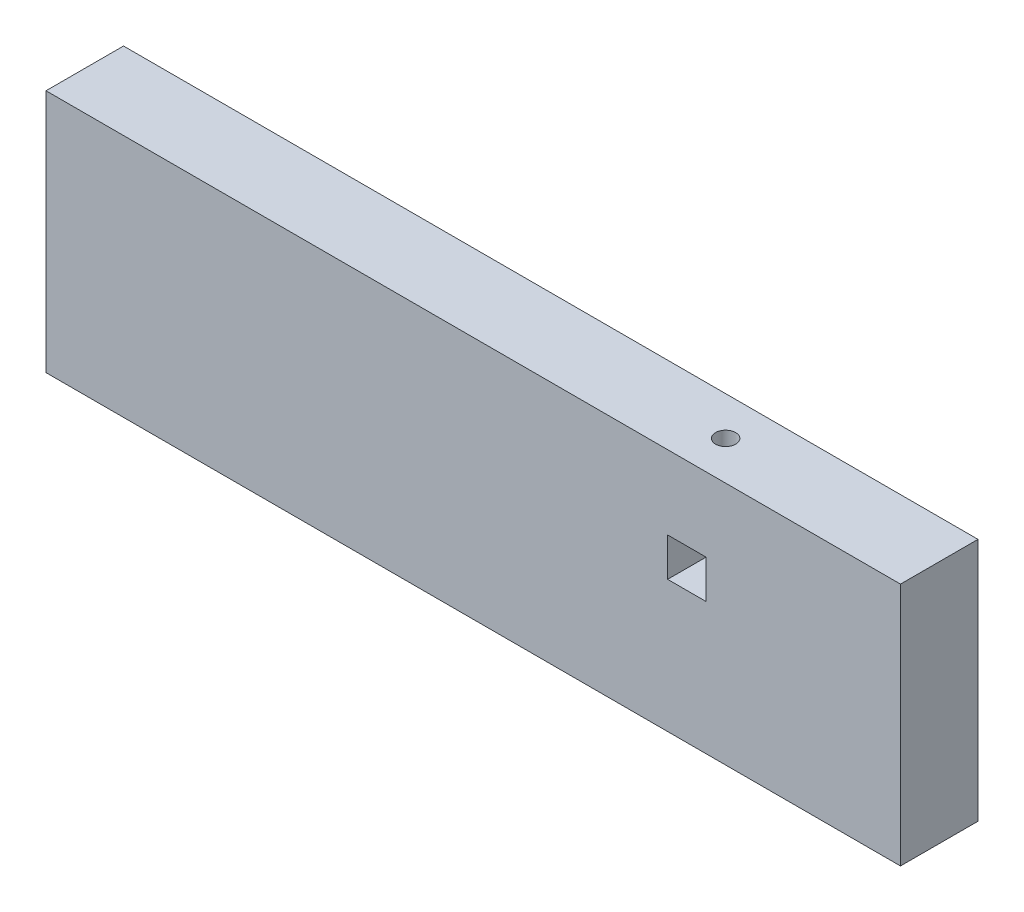
SolidWorks part; units mm, degrees
material "ABS"
ref_plane "Front Plane" through (0, 0, 0) normal (0, 0, 1) x (1, 0, 0)
ref_plane "Top Plane" through (0, 0, 0) normal (0, 1, 0) x (1, 0, 0)
ref_plane "Right Plane" through (0, 0, 0) normal (1, 0, 0) x (0, 0, -1)
sketch "Sketch1" plane through (0, 0, 0) normal (0, 0, 1) x (1, 0, 0)
  line L1 (-70, 40) -> (70, 40)
  line L2 (-70, 40) -> (-70, 0)
  line L3 (-70, 0) -> (70, 0)
  line L4 (70, 40) -> (70, 0)
  line L5 (31.85, 27.9) -> (38.15, 27.9)
  line L6 (31.85, 27.9) -> (31.85, 21.6)
  line L7 (31.85, 21.6) -> (38.15, 21.6)
  line L8 (38.15, 27.9) -> (38.15, 21.6)
  line L9 (32, 27.75) -> (38, 27.75) construction
  line L10 (32, 27.75) -> (32, 21.75) construction
  line L11 (32, 21.75) -> (38, 21.75) construction
  line L12 (38, 27.75) -> (38, 21.75) construction
  point P10 (0, 0)
  point P14 (35, 27.75)
  point P15 (35, 27.9)
  point P16 (32, 24.75)
  point P17 (31.85, 24.75)
  dimension "D1" = 6.3
  dimension "D2" = 140
  dimension "D3" = 40
  dimension "D4" = 21.6
  dimension "D5" = 32
  dimension "D6" = 6
extrude "Boss-Extrude1" add sketch "Sketch1" along normal blind 12.7 contours L1 L4 L3 L2
sketch "Sketch2" plane through (0, 40, 0) normal (0, 1, 0) x (1, 0, 0)
  line L0 (70, -12.7) -> (-70, -12.7) construction
  line L1 (38, -12.7) -> (32, -12.7) construction
  line L2 (38, -12.7) -> (38, 0) construction
  line L3 (38, 0) -> (32, 0) construction
  line L4 (32, -12.7) -> (32, 0) construction
  line L5 (70, 0) -> (-70, 0) construction
  line L6 (70, -12.7) -> (70, 0) construction
  circle A0 centre (35, -6.35) radius 2.5 construction
  point P12 (35, 0)
  point P14 (32, -6.35)
  dimension "D3" = 5
  dimension "D1" = 32
  dimension "D2" = 6
hole_wizard "Tap Drill for M4x0.7 Tap1" positions "3DSketch1" profile "Sketch3" hole size "M4x0.7" standard "ANSI Metric"
sketch3d "3DSketch1"
  point P0 (35, 40, 6.35)
sketch "Sketch3" plane through (35, 40, 6.35) normal (1, 0, 0) x (0, 0, 1)
  line L0 (0, 0) -> (0, 12.1)
  line L1 (0, 12.1) -> (1.65, 12.1)
  line L2 (1.65, 12.1) -> (1.65, 0)
  line L5 (1.65, 0) -> (0, 0)
  line L11 (0, -6.35) -> (0, 107.95) construction
  dimension "Thru Hole Dia." = 3.3
  dimension "Thru Hole Depth" = 12.1
sketch "Sketch4" plane through (0, 0, 0) normal (0, -1, 0) x (1, 0, 0)
  line L0 (-60, 6.35) -> (60, 6.35) construction
  line L2 (-70, 12.7) -> (70, 12.7)
  line L3 (-70, 12.7) -> (-70, 0)
  line L4 (-70, 0) -> (70, 0)
  line L5 (70, 12.7) -> (70, 0)
  circle A0 centre (0, 6.35) radius 2.5 construction
  circle A1 centre (60, 6.35) radius 2.5 construction
  circle A2 centre (-60, 6.35) radius 2.5 construction
  point P6 (0, 6.35)
  point P14 (70, 6.35)
  dimension "D1" = 5
  dimension "D2" = 120
hole_wizard "Tap Drill for M5x0.8 Tap2" positions "3DSketch2" profile "Sketch5" hole size "M5x0.8" standard "ANSI Metric"
sketch3d "3DSketch2"
  point P0 (-60, 0, 6.35)
  point P2 (0, 0, 6.35)
  point P4 (60, 0, 6.35)
sketch "Sketch5" plane through (-60, 0, 6.35) normal (1, 0, 0) x (0, 0, -1)
  line L0 (0, 0) -> (0, 8.2618)
  line L1 (0, 8.2618) -> (2.1, 7)
  line L2 (2.1, 7) -> (2.1, 0)
  line L5 (2.1, 0) -> (0, 0)
  line L10 (0, 8.2618) -> (-2.1, 7) construction
  line L11 (0, -6.35) -> (0, 107.95) construction
  dimension "Hole Dia." = 4.2
  dimension "Hole Depth" = 7
  dimension "Drill Angle" = 118
